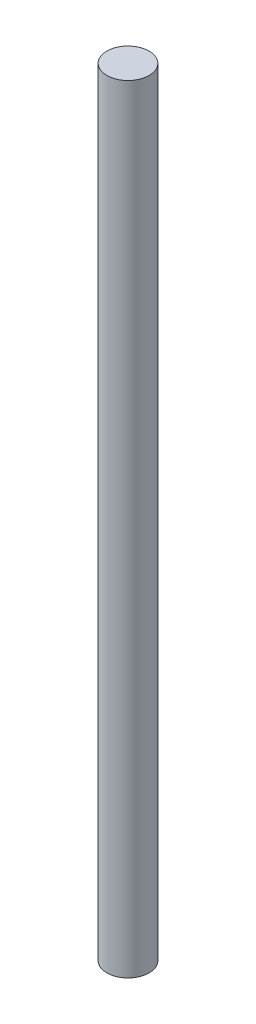
SolidWorks part; units mm, degrees
material "1060 Alloy"
ref_plane "Front Plane" through (0, 0, 0) normal (0, 0, 1) x (1, 0, 0)
ref_plane "Top Plane" through (0, 0, 0) normal (0, 1, 0) x (1, 0, 0)
ref_plane "Right Plane" through (0, 0, 0) normal (1, 0, 0) x (0, 0, -1)
sketch "Sketch1" plane through (0, 0, 0) normal (0, 1, 0) x (1, 0, 0)
  circle A0 centre (-5.3268, 0) radius 4
  dimension "D1" = 8
extrude "Boss-Extrude1" add sketch "Sketch1" along normal blind 147.09
